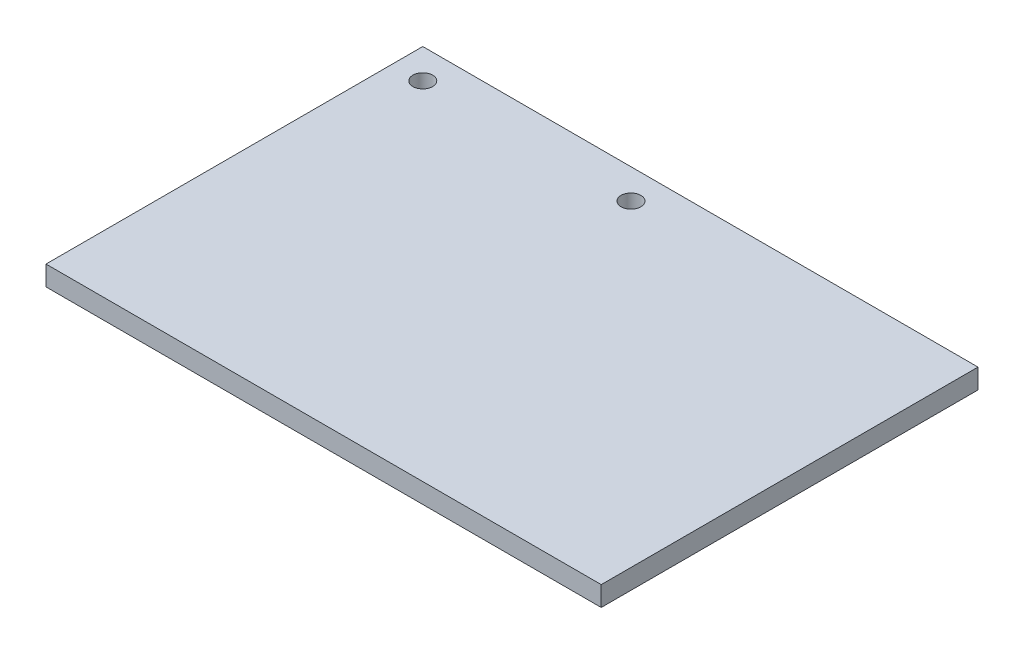
SolidWorks part; units mm, degrees
ref_plane "Alzado" through (0, 0, 0) normal (0, 0, 1) x (1, 0, 0)
ref_plane "Planta" through (0, 0, 0) normal (0, 1, 0) x (1, 0, 0)
ref_plane "Vista lateral" through (0, 0, 0) normal (1, 0, 0) x (0, 0, -1)
sketch "Croquis1" plane through (0, 0, 0) normal (0, 1, 0) x (1, 0, 0)
  line L1 (-140, -95) -> (140, -95)
  line L2 (-140, -95) -> (-140, 95)
  line L3 (-140, 95) -> (140, 95)
  line L4 (140, -95) -> (140, 95)
  line L5 (-140, -95) -> (140, 95) construction
  line L6 (-140, 95) -> (140, -95) construction
  point P0 (0, 0)
  dimension "D1" = 280
  dimension "D2" = 190
extrude "Saliente-Extruir1" add sketch "Croquis1" along normal blind 10
sketch "Croquis2" plane through (0, 10, 0) normal (0, 1, 0) x (1, 0, 0)
  line L0 (-140, 95) -> (-140, -95) construction
  line L1 (140, 95) -> (-140, 95) construction
  circle A0 centre (-125, 80) radius 5
  circle A1 centre (-20, 80) radius 5
  dimension "D1" = 15
  dimension "D3" = 120
  dimension "D2" = 15
  dimension "D4" = 15
extrude "Cortar-Extruir1" cut sketch "Croquis2" against normal up to surface (10 mm away) up to face at (0, 0, 0)
